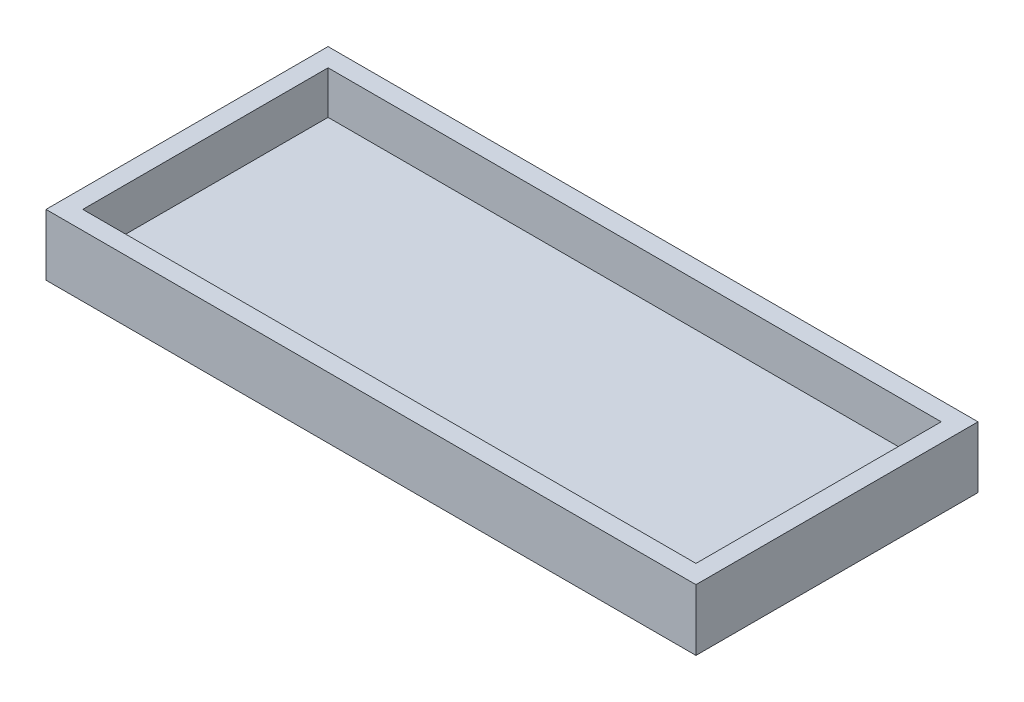
SolidWorks part; units mm, degrees
ref_plane "Front Plane" through (0, 0, 0) normal (0, 0, 1) x (1, 0, 0)
ref_plane "Top Plane" through (0, 0, 0) normal (0, 1, 0) x (1, 0, 0)
ref_plane "Right Plane" through (0, 0, 0) normal (1, 0, 0) x (0, 0, -1)
sketch "Sketch1" plane through (0, 0, 0) normal (0, 1, 0) x (1, 0, 0)
  line L1 (-53, -23) -> (53, -23)
  line L2 (-53, -23) -> (-53, 23)
  line L3 (-53, 23) -> (53, 23)
  line L4 (53, -23) -> (53, 23)
  line L5 (-53, -23) -> (53, 23) construction
  line L6 (-53, 23) -> (53, -23) construction
  point P0 (0, 0)
  dimension "D1" = 106
  dimension "D2" = 46
extrude "Boss-Extrude1" add sketch "Sketch1" along normal blind 10
ref_plane "Plane1" through (0, 10, 0) normal (0, 1, 0) x (1, 0, 0)
sketch "Sketch2" plane through (0, 10, 0) normal (0, 1, 0) x (1, 0, 0)
  line L0 (-53, 23) -> (-53, -23) construction
  line L1 (-50, -20) -> (50, -20)
  line L2 (-50, -20) -> (-50, 20)
  line L3 (-50, 20) -> (50, 20)
  line L4 (50, -20) -> (50, 20)
  line L5 (-50, -20) -> (50, 20) construction
  line L6 (-50, 20) -> (50, -20) construction
  line L7 (53, 23) -> (-53, 23) construction
  point P0 (0, 0)
  dimension "D1" = 3
  dimension "D2" = 3
extrude "Cut-Extrude1" cut sketch "Sketch2" against normal blind 7
